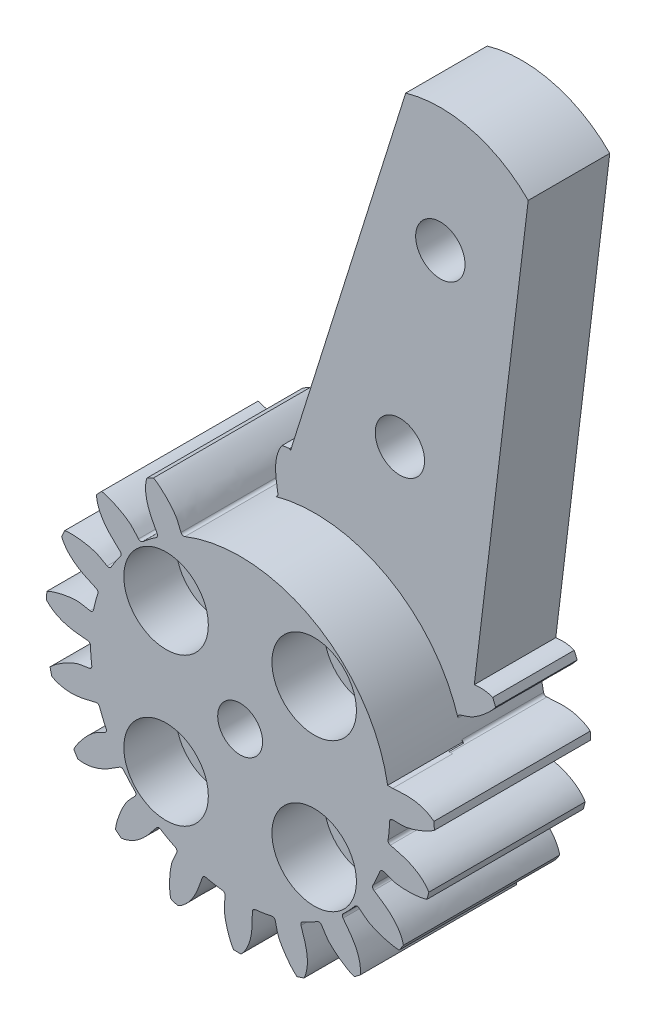
SolidWorks part; units mm, degrees
ref_plane "前视基准面" through (0, 0, 0) normal (0, 0, 1) x (1, 0, 0)
ref_plane "上视基准面" through (0, 0, 0) normal (0, 1, 0) x (1, 0, 0)
ref_plane "右视基准面" through (0, 0, 0) normal (1, 0, 0) x (0, 0, -1)
other "Configuration Table"
sketch "草图3" plane through (0, 0, 0) normal (0, 0, 1) x (1, 0, 0)
  circle A0 centre (0, 0) radius 13
  circle A1 centre (0, 0) radius 10
  dimension "D1" = 26
  dimension "D2" = 20
extrude "凸台-拉伸1" add sketch "草图3" along normal blind 4 contours A1 | A0 A1
sketch "草图6" plane through (0, 0, 4) normal (0, 0, 1) x (1, 0, 0)
  line L0 (0, 14.519) -> (0, -0.3622) construction
  line L5 (0, 0) -> (-1.6968, 12.8888) construction
  line L6 (-1.6968, 12.8888) -> (-1.8736, 14.2316)
  line L7 (-1.8736, 14.2316) -> (3.0009, 14.404)
  line L8 (3.0009, 14.404) -> (2.085, 12.8317)
  arc A0 (0.6559, 9.9785) -> (-0.4764, 9.9886) centre (0, 0) ccw
  circle A1 centre (0, 0) radius 13 construction
  arc A2 (0.6559, 9.9785) -> (0.8668, 10.1484) centre (0.669, 10.178) ccw
  arc A3 (-0.6854, 10.1744) -> (-0.4764, 9.9886) centre (-0.4859, 10.1884) ccw
  spline S0 degree 3 poles (-1.6968, 12.8888) (-1.3404, 12.4914) (-0.7219, 11.2236) (-0.7215, 10.6885) (-0.6854, 10.1744) knots 0 0 0 0 0.644244 0.940775 0.940775 0.940775 0.940775
  spline S1 degree 3 poles (2.085, 12.8317) (1.4718, 12.3854) (1.0735, 11.4242) (0.9081, 10.424) (0.8668, 10.1484) knots 0 0 0 0 0.67612 0.940775 0.940775 0.940775 0.940775
  dimension "D1" = 20
  dimension "D2" = 0.2
  dimension "D3" = 7.5
extrude "切除-拉伸2" cut sketch "草图6" against normal through all both
pattern_circular "阵列(圆周)4" count 19 over 360 about axis through (0, 0, 4) along (0, 0, 1) of "切除-拉伸2"
ref_plane "基准面3" through (0, 0, 2) normal (0, 0, 1) x (1, 0, 0)
sketch "草图8" plane through (0, 0, 0) normal (0, 0, -1) x (-1, 0, 0)
  line L1 (-4.9497, -4.9497) -> (4.9497, -4.9497) construction
  line L2 (-4.9497, -4.9497) -> (-4.9497, 4.9497) construction
  line L3 (-4.9497, 4.9497) -> (4.9497, 4.9497) construction
  line L4 (4.9497, -4.9497) -> (4.9497, 4.9497) construction
  line L5 (-4.9497, -4.9497) -> (4.9497, 4.9497) construction
  line L6 (-4.9497, 4.9497) -> (4.9497, -4.9497) construction
  circle A0 centre (0, 0) radius 1.5
  circle A1 centre (-4.9497, 4.9497) radius 1.5
  circle A2 centre (-4.9497, -4.9497) radius 1.5
  circle A3 centre (4.9497, -4.9497) radius 1.5
  circle A4 centre (4.9497, 4.9497) radius 1.5
  dimension "D1" = 3
  dimension "D3" = 3
  dimension "D4" = 3
  dimension "D5" = 3
  dimension "D6" = 3
  dimension "D2" = 14
extrude "切除-拉伸4" cut sketch "草图8" against normal through all both and the other way through all
sketch "草图9" plane through (0, 0, 0) normal (0, 0, -1) x (-1, 0, 0)
  line L0 (21.6161, 0) -> (-28.4343, 0) construction
  line L1 (0, 64.6203) -> (0, -26.1106) construction
  line L2 (11, 81.5593) -> (11, -8.562) construction
  line L6 (-16.7977, 56.2441) -> (-10, 0)
  line L7 (10.5, 96.6294) -> (10.5, -28.0536) construction
  line L8 (2.6197, 9.6508) -> (-6.0667, 37.3455)
  line L9 (10.5, 87.5322) -> (10.5, 84.5987)
  line L10 (10.5, 34.6087) -> (10.5, 31.6753)
  line L11 (10.5, 31.6753) -> (10.5, 31.5414)
  arc A0 (2.6197, 9.6508) -> (-10, 0) centre (0, 0) ccw
  circle A1 centre (11, 59.6037) radius 25 construction
  arc A3 (10.5, 84.5987) -> (10.5, 34.6087) centre (11, 59.6037) ccw
  arc A4 (-6.0667, 37.3455) -> (10.5, 31.5414) centre (11.008, 59.5368) ccw
  arc A6 (10.5, 87.5322) -> (-16.7977, 56.2441) centre (11.008, 59.5368) ccw
  point P22 (39, 59.6037)
  dimension "D1" = 50
  dimension "D3" = 11
  dimension "D4" = 0.5
sketch "草图13" plane through (0, 0, 0) normal (0, 0, -1) x (-1, 0, 0)
  circle A0 centre (-4.9497, -4.9497) radius 1.5 construction
  circle A1 centre (4.9497, -4.9497) radius 1.5 construction
  circle A2 centre (4.9497, 4.9497) radius 1.5 construction
  circle A3 centre (0, 0) radius 1.5 construction
  circle A4 centre (-4.9497, 4.9497) radius 1.5 construction
  circle A5 centre (-4.9497, -4.9497) radius 1.5
  circle A6 centre (4.9497, -4.9497) radius 1.5
  circle A7 centre (4.9497, 4.9497) radius 1.5
  circle A8 centre (0, 0) radius 1.5
  circle A9 centre (-4.9497, 4.9497) radius 1.5
  arc A61 (2.4754, 9.88) -> (2.6197, 9.6508) centre (2.6721, 9.8438) ccw
  arc A62 (2.4754, 9.88) -> (2.6197, 9.6508) centre (2.6721, 9.8438) ccw
  arc A63 (0.4764, 9.9886) -> (0.6854, 10.1744) centre (0.4859, 10.1884) ccw
  arc A64 (-11.8827, 5.2728) -> (-12.0778, 4.8089) centre (0, 0) ccw
  arc A65 (-12.9509, 1.1288) -> (-12.9849, 0.6267) centre (0, 0) ccw
  arc A66 (-9.9939, -0.3501) -> (-10.1963, -0.1571) centre (-10.1937, -0.3571) ccw
  arc A67 (-9.9939, -0.3501) -> (-9.8902, -1.4776) centre (0, 0) ccw
  arc A68 (-10.0421, -1.7019) -> (-9.8902, -1.4776) centre (-10.088, -1.5072) ccw
  arc A69 (-12.6157, -3.1375) -> (-12.4848, -3.6234) centre (0, 0) ccw
  arc A70 (-9.3387, -3.5761) -> (-9.5928, -3.4593) centre (-9.5255, -3.6476) ccw
  arc A71 (-9.3387, -3.5761) -> (-8.8746, -4.6089) centre (0, 0) ccw
  arc A72 (-8.9454, -4.8703) -> (-8.8746, -4.6089) centre (-9.052, -4.7011) ccw
  arc A73 (-10.9134, -7.0638) -> (-10.6318, -7.4809) centre (0, 0) ccw
  arc A74 (-7.6715, -6.4146) -> (-7.9498, -6.3867) centre (-7.825, -6.5429) ccw
  arc A75 (-7.6715, -6.4146) -> (-6.8972, -7.2408) centre (0, 0) ccw
  arc A76 (-6.8794, -7.511) -> (-6.8972, -7.2408) centre (-7.0351, -7.3856) ccw
  arc A77 (-8.0285, -10.2247) -> (-7.6267, -10.5277) centre (0, 0) ccw
  arc A78 (-5.1731, -8.558) -> (-5.4453, -8.6219) centre (-5.2765, -8.7292) ccw
  arc A79 (-5.1731, -8.558) -> (-4.1724, -9.088) centre (0, 0) ccw
  arc A80 (-4.0678, -9.3378) -> (-4.1724, -9.088) centre (-4.2559, -9.2697) ccw
  arc A81 (-4.2735, -12.2775) -> (-3.7951, -12.4337) centre (0, 0) ccw
  arc A82 (-2.114, -9.774) -> (-2.3508, -9.9228) centre (-2.1563, -9.9695) ccw
  arc A83 (-2.114, -9.774) -> (-0.9955, -9.9503) centre (0, 0) ccw
  arc A84 (-0.8154, -10.1526) -> (-0.9955, -9.9503) centre (-1.0154, -10.1493) ccw
  arc A85 (-0.0555, -12.9999) -> (0.4477, -12.9923) centre (0, 0) ccw
  arc A86 (1.1742, -9.9308) -> (0.9986, -10.1485) centre (1.1976, -10.1294) ccw
  arc A87 (1.1742, -9.9308) -> (2.2893, -9.7344) centre (0, 0) ccw
  arc A88 (2.5253, -9.8673) -> (2.2893, -9.7344) centre (2.3351, -9.9291) ccw
  arc A89 (4.1686, -12.3135) -> (4.6421, -12.143) centre (0, 0) ccw
  arc A90 (4.3351, -9.0115) -> (4.2397, -9.2744) centre (4.4218, -9.1917) ccw
  arc A91 (4.3351, -9.0115) -> (5.326, -8.4636) centre (0, 0) ccw
  arc A92 (5.5924, -8.5127) -> (5.326, -8.4636) centre (5.4326, -8.6329) ccw
  arc A93 (7.9409, -10.2928) -> (8.3333, -9.9777) centre (0, 0) ccw
  arc A94 (7.0262, -7.1156) -> (7.0213, -7.3953) centre (7.1667, -7.2579) ccw
  arc A95 (7.0262, -7.1156) -> (7.7856, -6.2757) centre (0, 0) ccw
  arc A96 (8.0535, -6.2356) -> (7.7856, -6.2757) centre (7.9413, -6.4012) ccw
  arc A97 (10.8527, -7.1567) -> (11.1216, -6.7313) centre (0, 0) ccw
  arc A98 (8.956, -4.4487) -> (9.0421, -4.7147) centre (9.1351, -4.5376) ccw
  arc A99 (8.956, -4.4487) -> (9.4015, -3.4077) centre (0, 0) ccw
  arc A100 (9.6418, -3.2828) -> (9.4015, -3.4077) centre (9.5895, -3.4758) ccw
  arc A101 (12.5885, -3.2451) -> (12.7046, -2.7554) centre (0, 0) ccw
  arc A102 (9.9152, -1.2996) -> (10.0831, -1.5233) centre (10.1135, -1.3256) ccw
  arc A103 (9.9152, -1.2996) -> (9.9985, -0.1704) centre (0, 0) ccw
  arc A104 (10.1853, 0.0258) -> (9.9985, -0.1704) centre (10.1985, -0.1738) ccw
  arc A105 (12.9601, 1.0182) -> (12.9109, 1.5191) centre (0, 0) ccw
  arc A106 (9.7999, 1.9902) -> (10.0314, 1.8332) centre (9.9959, 2.03) ccw
  arc A107 (9.7999, 1.9902) -> (9.5121, 3.0854) centre (0, 0) ccw
  arc A108 (9.6251, 3.3315) -> (9.5121, 3.0854) centre (9.7024, 3.1471) ccw
  arc A109 (11.9272, 5.1712) -> (11.7181, 5.629) centre (0, 0) ccw
  arc A110 (8.6227, 5.0644) -> (8.8926, 4.9911) centre (8.7952, 5.1657) ccw
  arc A111 (8.6227, 5.0644) -> (7.9949, 6.0068) centre (0, 0) ccw
  arc A112 (8.0218, 6.2763) -> (7.9949, 6.0068) centre (8.1548, 6.1269) ccw
  arc A113 (9.6019, 8.7638) -> (9.2555, 9.1288) centre (0, 0) ccw
  arc A114 (6.5111, 7.5898) -> (6.7902, 7.608) centre (6.6413, 7.7416) ccw
  arc A115 (6.5111, 7.5898) -> (5.6113, 8.2773) centre (0, 0) ccw
  arc A116 (5.5493, 8.5409) -> (5.6113, 8.2773) centre (5.7236, 8.4428) ccw
  arc A117 (6.236, 11.4067) -> (5.7899, 11.6395) centre (0, 0) ccw
  arc A118 (3.6939, 9.2927) -> (3.9519, 9.4006) centre (3.7678, 9.4786) ccw
  arc A119 (3.6939, 9.2927) -> (2.6197, 9.6508) centre (0, 0) ccw
  arc A120 (2.1944, 12.8134) -> (1.6968, 12.8888) centre (0, 0) ccw
  arc A125 (-11.8827, 5.2728) -> (-12.0778, 4.8089) centre (0, 0) ccw
  arc A126 (-12.9509, 1.1288) -> (-12.9849, 0.6267) centre (0, 0) ccw
  arc A127 (-9.9939, -0.3501) -> (-10.1963, -0.1571) centre (-10.1937, -0.3571) ccw
  arc A128 (-9.9939, -0.3501) -> (-9.8902, -1.4776) centre (0, 0) ccw
  arc A129 (-10.0421, -1.7019) -> (-9.8902, -1.4776) centre (-10.088, -1.5072) ccw
  arc A130 (-12.6157, -3.1375) -> (-12.4848, -3.6234) centre (0, 0) ccw
  arc A131 (-9.3387, -3.5761) -> (-9.5928, -3.4593) centre (-9.5255, -3.6476) ccw
  arc A132 (-9.3387, -3.5761) -> (-8.8746, -4.6089) centre (0, 0) ccw
  arc A133 (-8.9454, -4.8703) -> (-8.8746, -4.6089) centre (-9.052, -4.7011) ccw
  arc A134 (-10.9134, -7.0638) -> (-10.6318, -7.4809) centre (0, 0) ccw
  arc A135 (-7.6715, -6.4146) -> (-7.9498, -6.3867) centre (-7.825, -6.5429) ccw
  arc A136 (-7.6715, -6.4146) -> (-6.8972, -7.2408) centre (0, 0) ccw
  arc A137 (-6.8794, -7.511) -> (-6.8972, -7.2408) centre (-7.0351, -7.3856) ccw
  arc A138 (-8.0285, -10.2247) -> (-7.6267, -10.5277) centre (0, 0) ccw
  arc A139 (-5.1731, -8.558) -> (-5.4453, -8.6219) centre (-5.2765, -8.7292) ccw
  arc A140 (-5.1731, -8.558) -> (-4.1724, -9.088) centre (0, 0) ccw
  arc A141 (-4.0678, -9.3378) -> (-4.1724, -9.088) centre (-4.2559, -9.2697) ccw
  arc A142 (-4.2735, -12.2775) -> (-3.7951, -12.4337) centre (0, 0) ccw
  arc A143 (-2.114, -9.774) -> (-2.3508, -9.9228) centre (-2.1563, -9.9695) ccw
  arc A144 (-2.114, -9.774) -> (-0.9955, -9.9503) centre (0, 0) ccw
  arc A145 (-0.8154, -10.1526) -> (-0.9955, -9.9503) centre (-1.0154, -10.1493) ccw
  arc A146 (-0.0555, -12.9999) -> (0.4477, -12.9923) centre (0, 0) ccw
  arc A147 (1.1742, -9.9308) -> (0.9986, -10.1485) centre (1.1976, -10.1294) ccw
  arc A148 (1.1742, -9.9308) -> (2.2893, -9.7344) centre (0, 0) ccw
  arc A149 (2.5253, -9.8673) -> (2.2893, -9.7344) centre (2.3351, -9.9291) ccw
  arc A150 (4.1686, -12.3135) -> (4.6421, -12.143) centre (0, 0) ccw
  arc A151 (4.3351, -9.0115) -> (4.2397, -9.2744) centre (4.4218, -9.1917) ccw
  arc A152 (4.3351, -9.0115) -> (5.326, -8.4636) centre (0, 0) ccw
  arc A153 (5.5924, -8.5127) -> (5.326, -8.4636) centre (5.4326, -8.6329) ccw
  arc A154 (7.9409, -10.2928) -> (8.3333, -9.9777) centre (0, 0) ccw
  arc A155 (7.0262, -7.1156) -> (7.0213, -7.3953) centre (7.1667, -7.2579) ccw
  arc A156 (7.0262, -7.1156) -> (7.7856, -6.2757) centre (0, 0) ccw
  arc A157 (8.0535, -6.2356) -> (7.7856, -6.2757) centre (7.9413, -6.4012) ccw
  arc A158 (10.8527, -7.1567) -> (11.1216, -6.7313) centre (0, 0) ccw
  arc A159 (8.956, -4.4487) -> (9.0421, -4.7147) centre (9.1351, -4.5376) ccw
  arc A160 (8.956, -4.4487) -> (9.4015, -3.4077) centre (0, 0) ccw
  arc A161 (9.6418, -3.2828) -> (9.4015, -3.4077) centre (9.5895, -3.4758) ccw
  arc A162 (12.5885, -3.2451) -> (12.7046, -2.7554) centre (0, 0) ccw
  arc A163 (9.9152, -1.2996) -> (10.0831, -1.5233) centre (10.1135, -1.3256) ccw
  arc A164 (9.9152, -1.2996) -> (9.9985, -0.1704) centre (0, 0) ccw
  arc A165 (10.1853, 0.0258) -> (9.9985, -0.1704) centre (10.1985, -0.1738) ccw
  arc A166 (12.9601, 1.0182) -> (12.9109, 1.5191) centre (0, 0) ccw
  arc A167 (9.7999, 1.9902) -> (10.0314, 1.8332) centre (9.9959, 2.03) ccw
  arc A168 (9.7999, 1.9902) -> (9.5121, 3.0854) centre (0, 0) ccw
  arc A169 (9.6251, 3.3315) -> (9.5121, 3.0854) centre (9.7024, 3.1471) ccw
  arc A170 (11.9272, 5.1712) -> (11.7181, 5.629) centre (0, 0) ccw
  arc A171 (8.6227, 5.0644) -> (8.8926, 4.9911) centre (8.7952, 5.1657) ccw
  arc A172 (8.6227, 5.0644) -> (7.9949, 6.0068) centre (0, 0) ccw
  arc A173 (8.0218, 6.2763) -> (7.9949, 6.0068) centre (8.1548, 6.1269) ccw
  arc A174 (9.6019, 8.7638) -> (9.2555, 9.1288) centre (0, 0) ccw
  arc A175 (6.5111, 7.5898) -> (6.7902, 7.608) centre (6.6413, 7.7416) ccw
  arc A176 (6.5111, 7.5898) -> (5.6113, 8.2773) centre (0, 0) ccw
  arc A177 (5.5493, 8.5409) -> (5.6113, 8.2773) centre (5.7236, 8.4428) ccw
  arc A178 (6.236, 11.4067) -> (5.7899, 11.6395) centre (0, 0) ccw
  arc A179 (3.6939, 9.2927) -> (3.9519, 9.4006) centre (3.7678, 9.4786) ccw
  arc A180 (3.6939, 9.2927) -> (2.6197, 9.6508) centre (0, 0) ccw
  arc A181 (2.1944, 12.8134) -> (1.6968, 12.8888) centre (0, 0) ccw
  arc A208 (0.4764, 9.9886) -> (0.6854, 10.1744) centre (0.4859, 10.1884) ccw
  arc A209 (0.4764, 9.9886) -> (-0.6559, 9.9785) centre (0, 0) ccw
  arc A210 (0.4764, 9.9886) -> (-0.6559, 9.9785) centre (0, 0) ccw
  arc A211 (-0.8668, 10.1484) -> (-0.6559, 9.9785) centre (-0.669, 10.178) ccw
  arc A212 (-0.8668, 10.1484) -> (-0.6559, 9.9785) centre (-0.669, 10.178) ccw
  arc A213 (-2.085, 12.8317) -> (-2.5801, 12.7414) centre (0, 0) ccw
  arc A214 (-2.085, 12.8317) -> (-2.5801, 12.7414) centre (0, 0) ccw
  arc A215 (-2.7927, 9.6021) -> (-2.6553, 9.8457) centre (-2.8486, 9.7942) ccw
  arc A216 (-2.7927, 9.6021) -> (-2.6553, 9.8457) centre (-2.8486, 9.7942) ccw
  arc A217 (-2.7927, 9.6021) -> (-3.8603, 9.2248) centre (0, 0) ccw
  arc A218 (-2.7927, 9.6021) -> (-3.8603, 9.2248) centre (0, 0) ccw
  arc A219 (-4.115, 9.3171) -> (-3.8603, 9.2248) centre (-3.9375, 9.4093) ccw
  arc A220 (-4.115, 9.3171) -> (-3.8603, 9.2248) centre (-3.9375, 9.4093) ccw
  arc A221 (-6.1385, 11.4595) -> (-6.5774, 11.2133) centre (0, 0) ccw
  arc A222 (-6.1385, 11.4595) -> (-6.5774, 11.2133) centre (0, 0) ccw
  arc A223 (-5.7592, 8.1751) -> (-5.7084, 8.4501) centre (-5.8744, 8.3386) ccw
  arc A224 (-5.7592, 8.1751) -> (-5.7084, 8.4501) centre (-5.8744, 8.3386) ccw
  arc A225 (-5.7592, 8.1751) -> (-6.6465, 7.4716) centre (0, 0) ccw
  arc A226 (-5.7592, 8.1751) -> (-6.6465, 7.4716) centre (0, 0) ccw
  arc A227 (-6.9173, 7.4761) -> (-6.6465, 7.4716) centre (-6.7794, 7.621) ccw
  arc A228 (-6.9173, 7.4761) -> (-6.6465, 7.4716) centre (-6.7794, 7.621) ccw
  arc A229 (-9.5268, 8.8454) -> (-9.862, 8.47) centre (0, 0) ccw
  arc A230 (-9.5268, 8.8454) -> (-9.862, 8.47) centre (0, 0) ccw
  arc A231 (-8.1016, 5.8621) -> (-8.1428, 6.1387) centre (-8.2636, 5.9793) ccw
  arc A232 (-8.1016, 5.8621) -> (-8.1428, 6.1387) centre (-8.2636, 5.9793) ccw
  arc A233 (-8.1016, 5.8621) -> (-8.7124, 4.9086) centre (0, 0) ccw
  arc A234 (-8.1016, 5.8621) -> (-8.7124, 4.9086) centre (0, 0) ccw
  arc A235 (-8.97, 4.825) -> (-8.7124, 4.9086) centre (-8.8866, 5.0068) ccw
  arc A236 (-8.97, 4.825) -> (-8.7124, 4.9086) centre (-8.8866, 5.0068) ccw
  arc A237 (-9.566, 2.9139) -> (-9.6948, 3.1621) centre (-9.7574, 2.9722) ccw
  arc A238 (-9.566, 2.9139) -> (-9.6948, 3.1621) centre (-9.7574, 2.9722) ccw
  arc A239 (-9.566, 2.9139) -> (-9.8341, 1.8138) centre (0, 0) ccw
  arc A240 (-9.566, 2.9139) -> (-9.8341, 1.8138) centre (0, 0) ccw
  arc A241 (-10.0506, 1.651) -> (-9.8341, 1.8138) centre (-10.0308, 1.85) ccw
  arc A242 (-10.0506, 1.651) -> (-9.8341, 1.8138) centre (-10.0308, 1.85) ccw
  spline S32 degree 3 poles (-76.3342, 3003.971) (-3.9974, -65.0179) (15.1798, 58.9043) (-60.6825, -34.2876) (588.9166, -2933.2553) knots -15.237816 -15.237816 -15.237816 -15.237816 0.264655 14.573643 14.573643 14.573643 14.573643 only from (-8.97, 4.825) to (-11.8827, 5.2728)
  spline S33 degree 3 poles (2408.6489, -1766.7612) (-88.5535, 99.6812) (22.3881, -45.1845) (-22.7629, 27.6923) (2677.4181, -1330.5859) knots -9.363882 -9.363882 -9.363882 -9.363882 0.644244 6.363781 6.363781 6.363781 6.363781 only from (-12.0778, 4.8089) to (-9.6948, 3.1621)
  spline S34 degree 3 poles (-1047.586, 2816.4219) (17.3304, -62.793) (-4.7689, 60.6416) (-46.2614, -52.1334) (1509.4339, -2583.1026) knots -15.237816 -15.237816 -15.237816 -15.237816 0.264655 14.573643 14.573643 14.573643 14.573643 only from (-10.0506, 1.651) to (-12.9509, 1.1288)
  spline S35 degree 3 poles (2851.8081, -888.9462) (-116.1218, 65.5269) (35.8464, -35.4669) (-30.5212, 18.8008) (2964.3887, -389.1349) knots -9.363882 -9.363882 -9.363882 -9.363882 0.644244 6.363781 6.363781 6.363781 6.363781 only from (-12.9849, 0.6267) to (-10.1963, -0.1571)
  spline S36 degree 3 poles (-1905.3155, 2323.6697) (36.7803, -53.7635) (-24.2008, 55.8074) (-26.8272, -64.3297) (2266.3806, -1953.0305) knots -15.237816 -15.237816 -15.237816 -15.237816 0.264655 14.573643 14.573643 14.573643 14.573643 only from (-10.0421, -1.7019) to (-12.6157, -3.1375)
  spline S37 degree 3 poles (2985.9296, 85.1999) (-131.1066, 24.2718) (45.4203, -21.9059) (-34.9721, 7.8719) (2930.1218, 594.485) knots -9.363882 -9.363882 -9.363882 -9.363882 0.644244 6.363781 6.363781 6.363781 6.363781 only from (-12.4848, -3.6234) to (-9.5928, -3.4593)
  spline S38 degree 3 poles (-2556.5746, 1579.112) (52.2444, -38.9079) (-41.0101, 44.9257) (-4.4858, -69.5549) (2777.7299, -1111.3174) knots -15.237816 -15.237816 -15.237816 -15.237816 0.264655 14.573643 14.573643 14.573643 14.573643 only from (-8.9454, -4.8703) to (-10.9134, -7.0638)
  spline S39 degree 3 poles (2796.4793, 1050.1133) (-131.8839, -19.6136) (50.0721, -5.971) (-35.6332, -3.9101) (2578.3308, 1513.6831) knots -9.363882 -9.363882 -9.363882 -9.363882 0.644244 6.363781 6.363781 6.363781 6.363781 only from (-10.6318, -7.4809) to (-7.9498, -6.3867)
  spline S40 degree 3 poles (-2930.7892, 663.4329) (62.047, -19.836) (-53.3754, 29.1755) (18.3417, -67.2428) (2988.069, -149.1757) knots -15.237816 -15.237816 -15.237816 -15.237816 0.264655 14.573643 14.573643 14.573643 14.573643 only from (-6.8794, -7.511) to (-8.0285, -10.2247)
  spline S41 degree 3 poles (2303.9871, 1901.2306) (-118.3695, -61.3735) (49.2978, 10.6109) (-32.4329, -15.2683) (1947.1376, 2268.8502) knots -9.363882 -9.363882 -9.363882 -9.363882 0.644244 6.363781 6.363781 6.363781 6.363781 only from (-7.6267, -10.5277) to (-5.4453, -8.6219)
  spline S42 degree 3 poles (-2987.4072, -324.1394) (65.1259, 1.3854) (-59.9567, 10.2637) (39.1816, -57.6438) (2874.6044, 829.1314) knots -15.237816 -15.237816 -15.237816 -15.237816 0.264655 14.573643 14.573643 14.573643 14.573643 only from (-4.0678, -9.3378) to (-4.2735, -12.2775)
  spline S43 degree 3 poles (1561.8221, 2546.3201) (-92.028, -96.4826) (43.1814, 26.0429) (-25.718, -24.972) (1104.9418, 2778.1522) knots -9.363882 -9.363882 -9.363882 -9.363882 0.644244 6.363781 6.363781 6.363781 6.363781 only from (-3.7951, -12.4337) to (-2.3508, -9.9228)
  spline S44 degree 3 poles (-2720.2934, -1276.5862) (61.1474, 22.4567) (-60.0407, -9.7603) (55.7756, -41.7983) (2449.6319, 1717.5893) knots -15.237816 -15.237816 -15.237816 -15.237816 0.264655 14.573643 14.573643 14.573643 14.573643 only from (-0.8154, -10.1526) to (-0.0555, -12.9999)
  spline S45 degree 3 poles (650.4095, 2915.4763) (-55.7138, -121.1364) (32.3856, 38.6528) (-16.2162, -31.9696) (143.0085, 2986.3983) knots -9.363882 -9.363882 -9.363882 -9.363882 0.644244 6.363781 6.363781 6.363781 6.363781 only from (0.4477, -12.9923) to (0.9986, -10.1485)
  spline S46 degree 3 poles (-2158.3935, -2090.6951) (50.5426, 41.0944) (-53.6183, -28.7267) (66.3254, -21.4232) (1759.2037, 2419.9198) knots -15.237816 -15.237816 -15.237816 -15.237816 0.264655 14.573643 14.573643 14.573643 14.573643 only from (2.5253, -9.8673) to (4.1686, -12.3135)
  spline S47 degree 3 poles (-331.4851, 2968.6954) (-13.3622, -132.6631) (18.0803, 47.0741) (-4.957, -35.5027) (-834.4221, 2871.0218) knots -9.363882 -9.363882 -9.363882 -9.363882 0.644244 6.363781 6.363781 6.363781 6.363781 only from (4.6421, -12.143) to (4.2397, -9.2744)
  spline S48 degree 3 poles (-1362.5982, -2678.2447) (34.4607, 55.279) (-41.3856, -44.58) (69.6878, 1.2734) (878.1386, 2860.0144) knots -15.237816 -15.237816 -15.237816 -15.237816 0.264655 14.573643 14.573643 14.573643 14.573643 only from (5.5924, -8.5127) to (7.9409, -10.2928)
  spline S49 degree 3 poles (-1277.4581, 2700.2102) (30.4375, -129.8138) (1.8157, 50.3942) (6.8393, -35.1886) (-1721.43, 2444.5255) knots -9.363882 -9.363882 -9.363882 -9.363882 0.644244 6.363781 6.363781 6.363781 6.363781 only from (8.3333, -9.9777) to (7.0213, -7.3953)
  spline S50 degree 3 poles (-419.1443, -2975.5649) (14.6445, 63.4732) (-24.6681, -55.6024) (65.4985, 23.8319) (-98.0866, 2990.182) knots -15.237816 -15.237816 -15.237816 -15.237816 0.264655 14.573643 14.573643 14.573643 14.573643 only from (8.0535, -6.2356) to (10.8527, -7.1567)
  spline S51 degree 3 poles (-2084.9987, 2139.1154) (70.9387, -112.8971) (-14.6456, 48.2532) (17.8944, -31.0613) (-2421.8943, 1753.127) knots -9.363882 -9.363882 -9.363882 -9.363882 0.644244 6.363781 6.363781 6.363781 6.363781 only from (11.1216, -6.7313) to (9.0421, -4.7147)
  spline S52 degree 3 poles (569.7305, -2950.4365) (-6.7587, 64.7891) (-5.2775, -60.5995) (54.2113, 43.808) (-1063.6825, 2796.3171) knots -15.237816 -15.237816 -15.237816 -15.237816 0.264655 14.573643 14.573643 14.573643 14.573643 only from (9.6418, -3.2828) to (12.5885, -3.2451)
  spline S53 degree 3 poles (-2666.5974, 1346.2143) (103.7527, -83.7462) (-29.5199, 40.8833) (27.0105, -23.568) (-2859.9088, 871.7499) knots -9.363882 -9.363882 -9.363882 -9.363882 0.644244 6.363781 6.363781 6.363781 6.363781 only from (12.7046, -2.7554) to (10.0831, -1.5233)
  spline S54 degree 3 poles (1496.8661, -2605.5825) (-27.4295, 59.0841) (14.6851, -59.0296) (37.0496, 59.0367) (-1914.0119, 2299.4277) knots -15.237816 -15.237816 -15.237816 -15.237816 0.264655 14.573643 14.573643 14.573643 14.573643 only from (10.1853, 0.0258) to (12.9601, 1.0182)
  spline S55 degree 3 poles (-2959.2288, 407.4299) (125.3234, -45.5202) (-41.1952, 29.083) (33.1995, -13.5207) (-2988.0078, -104.0948) knots -9.363882 -9.363882 -9.363882 -9.363882 0.644244 6.363781 6.363781 6.363781 6.363781 only from (12.9109, 1.5191) to (10.0314, 1.8332)
  spline S56 degree 3 poles (2261.793, -1978.3733) (-45.1278, 46.9764) (33.0563, -51.063) (15.8729, 67.8679) (-2556.9284, 1553.3598) knots -15.237816 -15.237816 -15.237816 -15.237816 0.264655 14.573643 14.573643 14.573643 14.573643 only from (9.6251, 3.3315) to (11.9272, 5.1712)
  spline S57 degree 3 poles (-2931.1819, -575.5058) (133.3134, -2.3613) (-48.4064, 14.1312) (35.7908, -2.0083) (-2792.3098, -1068.6592) knots -9.363882 -9.363882 -9.363882 -9.363882 0.644244 6.363781 6.363781 6.363781 6.363781 only from (11.7181, 5.629) to (8.8926, 4.9911)
  spline S58 degree 3 poles (2781.6196, -1136.7766) (-57.9359, 29.7781) (47.8453, -37.5629) (-7.0238, 69.3446) (-2922.7621, 638.9612) knots -15.237816 -15.237816 -15.237816 -15.237816 0.264655 14.573643 14.573643 14.573643 14.573643 only from (8.0218, 6.2763) to (9.6019, 8.7638)
  spline S59 degree 3 poles (-2585.496, -1496.0765) (126.8569, 41.0534) (-50.372, -2.352) (34.5037, 9.7218) (-2294.0217, -1917.4178) knots -9.363882 -9.363882 -9.363882 -9.363882 0.644244 6.363781 6.363781 6.363781 6.363781 only from (9.2555, 9.1288) to (6.7902, 7.608)
  spline S60 degree 3 poles (3000.0145, -171.9925) (-64.4657, 9.3529) (57.4496, -19.9923) (-29.1594, 63.3067) (-2971.8691, -344.6788) knots -15.237816 -15.237816 -15.237816 -15.237816 0.264655 14.573643 14.573643 14.573643 14.573643 only from (5.5493, 8.5409) to (6.236, 11.4067)
  spline S61 degree 3 poles (-1959.6314, -2254.5241) (106.6534, 80.0194) (-46.879, -18.5803) (29.4775, 20.3983) (-1547.1407, -2558.3944) knots -9.363882 -9.363882 -9.363882 -9.363882 0.644244 6.363781 6.363781 6.363781 6.363781 only from (5.7899, 11.6395) to (3.9519, 9.4006)
  spline S62 degree 3 poles (2893.3113, 811.4297) (-64.0097, -12.0858) (60.8283, -0.2552) (-48.1351, 50.4086) (-2698.928, -1290.9675) knots -15.237816 -15.237816 -15.237816 -15.237816 0.264655 14.573643 14.573643 14.573643 14.573643 only from (2.4754, 9.88) to (2.1944, 12.8134)
  spline S63 degree 3 poles (-1121.4104, -2768.6591) (74.8924, 110.314) (-38.3059, -32.7952) (21.257, 28.8644) (-632.603, -2922.1293) knots -9.363882 -9.363882 -9.363882 -9.363882 0.644244 6.363781 6.363781 6.363781 6.363781 only from (1.6968, 12.8888) to (0.6854, 10.1744)
  spline S64 degree 3 poles (-8.97, 4.825) (-9.2233, 4.9412) (-10.1511, 5.3497) (-11.1736, 5.5421) (-11.8827, 5.2728) knots 0 0 0 0 0.264655 0.940775 0.940775 0.940775 0.940775
  spline S65 degree 3 poles (-12.0778, 4.8089) (-11.7801, 4.3658) (-10.7029, 3.455) (-10.1843, 3.3233) (-9.6948, 3.1621) knots 0 0 0 0 0.644244 0.940775 0.940775 0.940775 0.940775
  spline S66 degree 3 poles (-10.0506, 1.651) (-10.328, 1.6786) (-11.3382, 1.7638) (-12.3677, 1.6137) (-12.9509, 1.1288) knots 0 0 0 0 0.264655 0.940775 0.940775 0.940775 0.940775
  spline S67 degree 3 poles (-12.9849, 0.6267) (-12.5594, 0.3043) (-11.2449, -0.2074) (-10.7115, -0.1636) (-10.1963, -0.1571) knots 0 0 0 0 0.644244 0.940775 0.940775 0.940775 0.940775
  spline S68 degree 3 poles (-10.0421, -1.7019) (-10.3134, -1.7658) (-11.2966, -2.0133) (-12.2216, -2.4895) (-12.6157, -3.1375) knots 0 0 0 0 0.264655 0.940775 0.940775 0.940775 0.940775
  spline S69 degree 3 poles (-12.4848, -3.6234) (-11.9777, -3.7902) (-10.5682, -3.8474) (-10.078, -3.6328) (-9.5928, -3.4593) knots 0 0 0 0 0.644244 0.940775 0.940775 0.940775 0.940775
  spline S70 degree 3 poles (-8.9454, -4.8703) (-9.1813, -5.0189) (-10.0308, -5.5722) (-10.751, -6.323) (-10.9134, -7.0638) knots 0 0 0 0 0.264655 0.940775 0.940775 0.940775 0.940775
  spline S71 degree 3 poles (-10.6318, -7.4809) (-10.098, -7.474) (-8.7464, -7.0704) (-8.3524, -6.7083) (-7.9498, -6.3867) knots 0 0 0 0 0.644244 0.940775 0.940775 0.940775 0.940775
  spline S72 degree 3 poles (-6.8794, -7.511) (-7.0542, -7.7281) (-7.678, -8.5272) (-8.1155, -9.4712) (-8.0285, -10.2247) knots 0 0 0 0 0.264655 0.940775 0.940775 0.940775 0.940775
  spline S73 degree 3 poles (-7.6267, -10.5277) (-7.1241, -10.3479) (-5.9767, -9.5273) (-5.7217, -9.0568) (-5.4453, -8.6219) knots 0 0 0 0 0.644244 0.940775 0.940775 0.940775 0.940775
  spline S74 degree 3 poles (-4.0678, -9.3378) (-4.1626, -9.5998) (-4.4932, -10.5582) (-4.6004, -11.5931) (-4.2735, -12.2775) knots 0 0 0 0 0.264655 0.940775 0.940775 0.940775 0.940775
  spline S75 degree 3 poles (-3.7951, -12.4337) (-3.3781, -12.1004) (-2.5593, -10.9517) (-2.4709, -10.4239) (-2.3508, -9.9228) knots 0 0 0 0 0.644244 0.940775 0.940775 0.940775 0.940775
  spline S76 degree 3 poles (-0.8154, -10.1526) (-0.82, -10.4313) (-0.8215, -11.4451) (-0.5869, -12.4587) (-0.0555, -12.9999) knots 0 0 0 0 0.264655 0.940775 0.940775 0.940775 0.940775
  spline S77 degree 3 poles (0.4477, -12.9923) (0.7339, -12.5416) (1.1353, -11.1893) (1.0476, -10.6614) (0.9986, -10.1485) knots 0 0 0 0 0.644244 0.940775 0.940775 0.940775 0.940775
  spline S78 degree 3 poles (2.5253, -9.8673) (2.6114, -10.1324) (2.9393, -11.0917) (3.4902, -11.9742) (4.1686, -12.3135) knots 0 0 0 0 0.264655 0.940775 0.940775 0.940775 0.940775
  spline S79 degree 3 poles (4.6421, -12.143) (4.7664, -11.6238) (4.707, -10.2144) (4.4526, -9.7436) (4.2397, -9.2744) knots 0 0 0 0 0.644244 0.940775 0.940775 0.940775 0.940775
  spline S80 degree 3 poles (5.5924, -8.5127) (5.7599, -8.7354) (6.3815, -9.5364) (7.1892, -10.1922) (7.9409, -10.2928) knots 0 0 0 0 0.264655 0.940775 0.940775 0.940775 0.940775
  spline S81 degree 3 poles (8.3333, -9.9777) (8.2824, -9.4463) (7.7686, -8.1326) (7.3751, -7.7699) (7.0213, -7.3953) knots 0 0 0 0 0.644244 0.940775 0.940775 0.940775 0.940775
  spline S82 degree 3 poles (8.0535, -6.2356) (8.2842, -6.3919) (9.1322, -6.9476) (10.109, -7.3056) (10.8527, -7.1567) knots 0 0 0 0 0.264655 0.940775 0.940775 0.940775 0.940775
  spline S83 degree 3 poles (11.1216, -6.7313) (10.9008, -6.2452) (9.9883, -5.1695) (9.4984, -4.9542) (9.0421, -4.7147) knots 0 0 0 0 0.644244 0.940775 0.940775 0.940775 0.940775
  spline S84 degree 3 poles (9.6418, -3.2828) (9.9108, -3.3557) (10.8932, -3.6059) (11.9334, -3.6274) (12.5885, -3.2451) knots 0 0 0 0 0.264655 0.940775 0.940775 0.940775 0.940775
  spline S85 degree 3 poles (12.7046, -2.7554) (12.338, -2.3673) (11.1256, -1.6462) (10.5924, -1.6017) (10.0831, -1.5233) knots 0 0 0 0 0.644244 0.940775 0.940775 0.940775 0.940775
  spline S86 degree 3 poles (10.1853, 0.0258) (10.4634, 0.0442) (11.4739, 0.1265) (12.4646, 0.4439) (12.9601, 1.0182) knots 0 0 0 0 0.264655 0.940775 0.940775 0.940775 0.940775
  spline S87 degree 3 poles (12.9109, 1.5191) (12.4382, 1.7671) (11.0573, 2.0555) (10.5385, 1.9245) (10.0314, 1.8332) knots 0 0 0 0 0.644244 0.940775 0.940775 0.940775 0.940775
  spline S88 degree 3 poles (9.6251, 3.3315) (9.8821, 3.4392) (10.8111, 3.8452) (11.6451, 4.4672) (11.9272, 5.1712) knots 0 0 0 0 0.264655 0.940775 0.940775 0.940775 0.940775
  spline S89 degree 3 poles (11.7181, 5.629) (11.1905, 5.71) (9.7908, 5.5344) (9.3426, 5.242) (8.8926, 4.9911) knots 0 0 0 0 0.644244 0.940775 0.940775 0.940775 0.940775
  spline S90 degree 3 poles (8.0218, 6.2763) (8.23, 6.4616) (8.9768, 7.1472) (9.5637, 8.0063) (9.6019, 8.7638) knots 0 0 0 0 0.264655 0.940775 0.940775 0.940775 0.940775
  spline S91 degree 3 poles (9.2555, 9.1288) (8.7301, 9.0342) (7.4633, 8.4136) (7.1343, 7.9916) (6.7902, 7.608) knots 0 0 0 0 0.644244 0.940775 0.940775 0.940775 0.940775
  spline S92 degree 3 poles (5.5493, 8.5409) (5.6859, 8.7838) (6.1697, 9.6747) (6.4459, 10.6778) (6.236, 11.4067) knots 0 0 0 0 0.264655 0.940775 0.940775 0.940775 0.940775
  spline S93 degree 3 poles (5.7899, 11.6395) (5.3237, 11.3793) (4.327, 10.3811) (4.1529, 9.8751) (3.9519, 9.4006) knots 0 0 0 0 0.644244 0.940775 0.940775 0.940775 0.940775
  spline S94 degree 3 poles (2.4754, 9.88) (2.5258, 10.1541) (2.6941, 11.1538) (2.6295, 12.1922) (2.1944, 12.8134) knots 0 0 0 0 0.264655 0.940775 0.940775 0.940775 0.940775
  spline S95 degree 3 poles (1.6968, 12.8888) (1.3404, 12.4914) (0.7219, 11.2236) (0.7215, 10.6885) (0.6854, 10.1744) knots 0 0 0 0 0.644244 0.940775 0.940775 0.940775 0.940775
  spline S102 degree 3 poles (1649.3402, 1140.0634) (-42.9095, -25.7332) (43.8632, 17.3008) (-48.1315, 30.3649) (-1434.7698, -1382.0657) knots -13.323382 -13.323382 -13.323382 -13.323382 0.264655 12.747684 12.747684 12.747684 12.747684 only from (-0.8668, 10.1484) to (-2.085, 12.8317)
  spline S103 degree 3 poles (-0.8668, 10.1484) (-0.9081, 10.424) (-1.0735, 11.4242) (-1.4718, 12.3854) (-2.085, 12.8317) knots 0 0 0 0 0.264655 0.940775 0.940775 0.940775 0.940775
  spline S104 degree 3 poles (-99.8661, -1984.7428) (26.219, 103.5176) (-20.3488, -30.4749) (7.6201, 27.6344) (237.381, -1975.6294) knots -8.147056 -8.147056 -8.147056 -8.147056 0.644244 5.645993 5.645993 5.645993 5.645993 only from (-2.5801, 12.7414) to (-2.6553, 9.8457)
  spline S105 degree 3 poles (-2.5801, 12.7414) (-2.7882, 12.2498) (-2.9615, 10.8498) (-2.7881, 10.3436) (-2.6553, 9.8457) knots 0 0 0 0 0.644244 0.940775 0.940775 0.940775 0.940775
  spline S106 degree 3 poles (1189.7964, 1613.8315) (-32.229, -38.2716) (35.8691, 30.6057) (-55.3831, 13.0914) (-908.274, -1773.0506) knots -13.323382 -13.323382 -13.323382 -13.323382 0.264655 12.747684 12.747684 12.747684 12.747684 only from (-4.115, 9.3171) to (-6.1385, 11.4595)
  spline S107 degree 3 poles (-4.115, 9.3171) (-4.2436, 9.5644) (-4.7248, 10.4567) (-5.4135, 11.2365) (-6.1385, 11.4595) knots 0 0 0 0 0.264655 0.940775 0.940775 0.940775 0.940775
  spline S108 degree 3 poles (549.9899, -1909.6304) (-8.8137, 106.4221) (-9.3511, -35.4309) (-1.7656, 28.6113) (866.0049, -1791.5069) knots -8.147056 -8.147056 -8.147056 -8.147056 0.644244 5.645993 5.645993 5.645993 5.645993 only from (-6.5774, 11.2133) to (-5.7084, 8.4501)
  spline S109 degree 3 poles (-6.5774, 11.2133) (-6.6146, 10.6807) (-6.324, 9.3003) (-5.9956, 8.8778) (-5.7084, 8.4501) knots 0 0 0 0 0.644244 0.940775 0.940775 0.940775 0.940775
  spline S110 degree 3 poles (601.3197, 1912.7159) (-18.056, -46.6627) (23.9879, 40.5941) (-56.633, -5.6008) (-283.3527, -1971.8979) knots -13.323382 -13.323382 -13.323382 -13.323382 0.264655 12.747684 12.747684 12.747684 12.747684 only from (-6.9173, 7.4761) to (-9.5268, 8.8454)
  spline S111 degree 3 poles (-6.9173, 7.4761) (-7.1192, 7.6683) (-7.8641, 8.3559) (-8.7687, 8.8699) (-9.5268, 8.8454) knots 0 0 0 0 0.264655 0.940775 0.940775 0.940775 0.940775
  spline S112 degree 3 poles (1140.2459, -1627.58) (-42.8914, 97.794) (2.66, -36.5475) (-10.9601, 26.4878) (1400.7837, -1413.2468) knots -8.147056 -8.147056 -8.147056 -8.147056 0.644244 5.645993 5.645993 5.645993 5.645993 only from (-9.862, 8.47) to (-8.1428, 6.1387)
  spline S113 degree 3 poles (-9.862, 8.47) (-9.7242, 7.9542) (-9.0012, 6.743) (-8.5534, 6.45) (-8.1428, 6.1387) knots 0 0 0 0 0.644244 0.940775 0.940775 0.940775 0.940775
  dimension "D1" = 0
extrude "凸台-拉伸6" add sketch "草图13" along normal blind 6.45
sketch "草图14" plane through (0, 0, 4) normal (0, 0, 1) x (1, 0, 0)
  circle A0 centre (4.9497, -4.9497) radius 2.825
  circle A1 centre (-4.9497, -4.9497) radius 2.825
  circle A2 centre (-4.9497, 4.9497) radius 2.825
  circle A3 centre (4.9497, 4.9497) radius 2.825
  dimension "D1" = 5.65
extrude "切除-拉伸5" cut sketch "草图14" against normal blind 3.5
extrude "凸台-拉伸7" add sketch "草图9" against normal up to surface (4 mm away) up to face at (7.7747, 4.9497, 4)
sketch "草图15" plane through (0, 0, 0) normal (0, 0, -1) x (-1, 0, 0)
  line L4 (1.6292, 12.8088) -> (-6.0667, 37.3455)
  line L5 (10.5, 31.5414) -> (10.5, 34.6087)
  line L6 (10.5, 84.5987) -> (10.5, 87.5322)
  line L7 (-16.7977, 56.2441) -> (-10.6514, 5.3898)
  line L8 (1.6292, 12.8088) -> (-6.0667, 37.3455)
  line L9 (10.5, 31.5414) -> (10.5, 34.6087)
  line L10 (10.5, 84.5987) -> (10.5, 87.5322)
  line L11 (-16.7977, 56.2441) -> (-10.6514, 5.3898)
  arc A18 (0.4764, 9.9886) -> (0.6854, 10.1744) centre (0.4859, 10.1884) ccw
  arc A19 (-6.0667, 37.3455) -> (10.5, 31.5414) centre (11.008, 59.5368) ccw
  arc A20 (10.5, 84.5987) -> (10.5, 34.6087) centre (11, 59.6037) ccw
  arc A21 (10.5, 87.5322) -> (-16.7977, 56.2441) centre (11.008, 59.5368) ccw
  arc A22 (-8.97, 4.825) -> (-8.7124, 4.9086) centre (-8.8866, 5.0068) ccw
  arc A23 (-8.1016, 5.8621) -> (-8.7124, 4.9086) centre (0, 0) ccw
  arc A24 (-8.1016, 5.8621) -> (-8.1428, 6.1387) centre (-8.2636, 5.9793) ccw
  arc A25 (-9.5268, 8.8454) -> (-9.862, 8.47) centre (0, 0) ccw
  arc A26 (-6.9173, 7.4761) -> (-6.6465, 7.4716) centre (-6.7794, 7.621) ccw
  arc A27 (-5.7592, 8.1751) -> (-6.6465, 7.4716) centre (0, 0) ccw
  arc A28 (-5.7592, 8.1751) -> (-5.7084, 8.4501) centre (-5.8744, 8.3386) ccw
  arc A29 (-6.1385, 11.4595) -> (-6.5774, 11.2133) centre (0, 0) ccw
  arc A30 (-4.115, 9.3171) -> (-3.8603, 9.2248) centre (-3.9375, 9.4093) ccw
  arc A31 (-2.7927, 9.6021) -> (-3.8603, 9.2248) centre (0, 0) ccw
  arc A32 (-2.7927, 9.6021) -> (-2.6553, 9.8457) centre (-2.8486, 9.7942) ccw
  arc A33 (-2.085, 12.8317) -> (-2.5801, 12.7414) centre (0, 0) ccw
  arc A34 (-0.8668, 10.1484) -> (-0.6559, 9.9785) centre (-0.669, 10.178) ccw
  arc A35 (0.4764, 9.9886) -> (-0.6559, 9.9785) centre (0, 0) ccw
  arc A36 (0.4764, 9.9886) -> (0.6854, 10.1744) centre (0.4859, 10.1884) ccw
  arc A37 (-6.0667, 37.3455) -> (10.5, 31.5414) centre (11.008, 59.5368) ccw
  arc A38 (10.5, 84.5987) -> (10.5, 34.6087) centre (11, 59.6037) ccw
  arc A39 (10.5, 87.5322) -> (-16.7977, 56.2441) centre (11.008, 59.5368) ccw
  arc A40 (-8.97, 4.825) -> (-8.7124, 4.9086) centre (-8.8866, 5.0068) ccw
  arc A41 (-8.1016, 5.8621) -> (-8.7124, 4.9086) centre (0, 0) ccw
  arc A42 (-8.1016, 5.8621) -> (-8.1428, 6.1387) centre (-8.2636, 5.9793) ccw
  arc A43 (-9.5268, 8.8454) -> (-9.862, 8.47) centre (0, 0) ccw
  arc A44 (-6.9173, 7.4761) -> (-6.6465, 7.4716) centre (-6.7794, 7.621) ccw
  arc A45 (-5.7592, 8.1751) -> (-6.6465, 7.4716) centre (0, 0) ccw
  arc A46 (-5.7592, 8.1751) -> (-5.7084, 8.4501) centre (-5.8744, 8.3386) ccw
  arc A47 (-6.1385, 11.4595) -> (-6.5774, 11.2133) centre (0, 0) ccw
  arc A48 (-4.115, 9.3171) -> (-3.8603, 9.2248) centre (-3.9375, 9.4093) ccw
  arc A49 (-2.7927, 9.6021) -> (-3.8603, 9.2248) centre (0, 0) ccw
  arc A50 (-2.7927, 9.6021) -> (-2.6553, 9.8457) centre (-2.8486, 9.7942) ccw
  arc A51 (-2.085, 12.8317) -> (-2.5801, 12.7414) centre (0, 0) ccw
  arc A52 (-0.8668, 10.1484) -> (-0.6559, 9.9785) centre (-0.669, 10.178) ccw
  arc A53 (0.4764, 9.9886) -> (-0.6559, 9.9785) centre (0, 0) ccw
  spline S8 degree 3 poles (-849.4221, -3898.2694) (25.8115, 33.6135) (-46.4765, -42.2531) (89.5076, 128.7392) (-1506.0777, -3691.9137) knots -5.953891 -5.953891 -5.953891 -5.953891 0.336874 11.314689 11.314689 11.314689 11.314689 only from (0.6854, 10.1744) to (1.6292, 12.8088)
  spline S9 degree 3 poles (809.0402, -3908.8039) (-68.3121, -43.899) (20.2334, 70.26) (-6.2081, -78.264) (-99.5263, 4003.6413) knots -15.475241 -15.475241 -15.475241 -15.475241 0.288374 17.315794 17.315794 17.315794 17.315794 only from (-10.6514, 5.3898) to (-8.97, 4.825)
  spline S10 degree 3 poles (2798.9635, -2843.3132) (-14.0226, 39.9939) (9.9525, -62.0183) (-58.8188, 145.3423) (2266.8926, -3279.965) knots -5.994273 -5.994273 -5.994273 -5.994273 0.296531 11.274177 11.274177 11.274177 11.274177 only from (-8.1428, 6.1387) to (-9.862, 8.47)
  spline S11 degree 3 poles (-503.9652, -3959.5499) (-78.8632, -19.3385) (41.9497, 59.8823) (-31.2836, -72.007) (1205.828, 3818.9711) knots -15.087282 -15.087282 -15.087282 -15.087282 0.67612 17.703456 17.703456 17.703456 17.703456 only from (-9.5268, 8.8454) to (-6.9173, 7.4761)
  spline S12 degree 3 poles (1724.0857, -3598.0766) (-0.2769, 42.38) (-10.724, -61.8895) (-8.4393, 156.5657) (1079.0632, -3838.3063) knots -5.994273 -5.994273 -5.994273 -5.994273 0.296531 11.274177 11.274177 11.274177 11.274177 only from (-5.7084, 8.4501) to (-6.5774, 11.2133)
  spline S13 degree 3 poles (-1762.3227, -3581.3733) (-80.8693, 7.3162) (59.1205, 43.0167) (-52.9692, -57.9477) (2380.5109, 3220.517) knots -15.087282 -15.087282 -15.087282 -15.087282 0.67612 17.703456 17.703456 17.703456 17.703456 only from (-6.1385, 11.4595) to (-4.115, 9.3171)
  spline S14 degree 3 poles (462.3764, -3962.9326) (13.4989, 40.1737) (-30.2385, -55.0541) (42.8548, 150.8228) (-225.6995, -3980.7075) knots -5.994273 -5.994273 -5.994273 -5.994273 0.296531 11.274177 11.274177 11.274177 11.274177 only from (-2.6553, 9.8457) to (-2.5801, 12.7414)
  spline S15 degree 3 poles (-2829.7053, -2815.0994) (-74.1121, 33.178) (69.8846, 21.4895) (-68.9148, -37.6089) (3297.2284, 2273.0699) knots -15.087282 -15.087282 -15.087282 -15.087282 0.67612 17.703456 17.703456 17.703456 17.703456 only from (-2.085, 12.8317) to (-0.8668, 10.1484)
  spline S16 degree 3 poles (0.6854, 10.1744) (0.7215, 10.6885) (0.7218, 11.2006) (1.2885, 12.384) (1.6292, 12.8088) knots 0.040343 0.040343 0.040343 0.040343 0.336874 0.940775 0.940775 0.940775 0.940775
  spline S17 degree 3 poles (-10.6514, 5.3898) (-10.3469, 5.3468) (-9.7687, 5.1813) (-9.2233, 4.9412) (-8.97, 4.825) knots 0 0 0 0 0.288374 0.553029 0.553029 0.553029 0.553029
  spline S18 degree 3 poles (-8.1428, 6.1387) (-8.5534, 6.45) (-9.0012, 6.743) (-9.7242, 7.9542) (-9.862, 8.47) knots 0 0 0 0 0.296531 0.940775 0.940775 0.940775 0.940775
  spline S19 degree 3 poles (-9.5268, 8.8454) (-8.7687, 8.8699) (-7.8641, 8.3559) (-7.1192, 7.6683) (-6.9173, 7.4761) knots 0 0 0 0 0.67612 0.940775 0.940775 0.940775 0.940775
  spline S20 degree 3 poles (-5.7084, 8.4501) (-5.9956, 8.8778) (-6.324, 9.3003) (-6.6146, 10.6807) (-6.5774, 11.2133) knots 0 0 0 0 0.296531 0.940775 0.940775 0.940775 0.940775
  spline S21 degree 3 poles (-6.1385, 11.4595) (-5.4135, 11.2365) (-4.7248, 10.4567) (-4.2436, 9.5644) (-4.115, 9.3171) knots 0 0 0 0 0.67612 0.940775 0.940775 0.940775 0.940775
  spline S22 degree 3 poles (-2.6553, 9.8457) (-2.7881, 10.3436) (-2.9615, 10.8498) (-2.7882, 12.2498) (-2.5801, 12.7414) knots 0 0 0 0 0.296531 0.940775 0.940775 0.940775 0.940775
  spline S23 degree 3 poles (-2.085, 12.8317) (-1.4718, 12.3854) (-1.0735, 11.4242) (-0.9081, 10.424) (-0.8668, 10.1484) knots 0 0 0 0 0.67612 0.940775 0.940775 0.940775 0.940775
  dimension "D1" = 0
extrude "凸台-拉伸8" add sketch "草图15" along normal up to surface (6.45 mm away) up to face at (0, 0, -6.45)
sketch "草图16" plane through (0, 0, -6.45) normal (0, 0, -1) x (-1, 0, 0)
  line L0 (0, 0) -> (0, 20) construction
  line L1 (-19.6216, 20.3655) -> (5.2081, 25.6432) construction
  line L2 (-8.3823, 29.3997) -> (-5.6795, 16.6838) construction
  circle A0 centre (-5.6795, 16.6838) radius 1.65
  circle A1 centre (-8.3823, 29.3997) radius 1.65
  dimension "D1" = 6.5
  dimension "D5" = 3.3
  dimension "D6" = 3.3
  dimension "D2" = 12
  dimension "D3" = 13
  dimension "D4" = 24
extrude "切除-拉伸6" cut sketch "草图16" against normal through all both and the other way through all
sketch "草图17" plane through (0, 0, -6.45) normal (0, 0, -1) x (-1, 0, 0)
  line L0 (-10.6514, 5.3898) -> (-16.7977, 56.2441) construction
  line L1 (-14.2578, 35.2287) -> (-16.7977, 56.2441)
  line L2 (10.5, 34.6087) -> (10.5, 31.5414)
  line L3 (10.5, 87.5322) -> (10.5, 84.5987)
  arc A0 (-6.0667, 37.3455) -> (-14.2578, 35.2287) centre (-8.3823, 29.3997) ccw
  arc A1 (10.5, 87.5322) -> (-16.7977, 56.2441) centre (11.008, 59.5368) ccw construction
  arc A2 (-6.0667, 37.3455) -> (10.5, 31.5414) centre (11.008, 59.5368) ccw construction
  arc A3 (10.5, 84.5987) -> (10.5, 34.6087) centre (11, 59.6037) ccw construction
  arc A4 (10.5, 87.5322) -> (-16.7977, 56.2441) centre (11.008, 59.5368) ccw
  arc A5 (-6.0667, 37.3455) -> (10.5, 31.5414) centre (11.008, 59.5368) ccw
  arc A6 (10.5, 84.5987) -> (10.5, 34.6087) centre (11, 59.6037) ccw
extrude "切除-拉伸7" cut sketch "草图17" against normal through all both and the other way through all
sketch "草图18" plane through (0, 0, 4) normal (0, 0, 1) x (1, 0, 0)
  line L0 (-2.6197, 9.6508) -> (-5.2377, 22.529)
  line L1 (-5.2377, 22.529) -> (3.7923, 38.4358)
  line L2 (3.7923, 38.4358) -> (15.9481, 39.6166)
  line L3 (15.9481, 39.6166) -> (17.0595, 22.529)
  line L4 (17.0595, 22.529) -> (15.2535, 8.5672)
  line L6 (9.8602, 1.666) -> (10.2013, 1.6655)
  line L7 (10.2013, 1.6655) -> (15.2535, 8.5672)
  arc A0 (9.8602, 1.666) -> (-2.6197, 9.6508) centre (0, 0) ccw
extrude "切除-拉伸8" cut sketch "草图18" against normal blind 5
